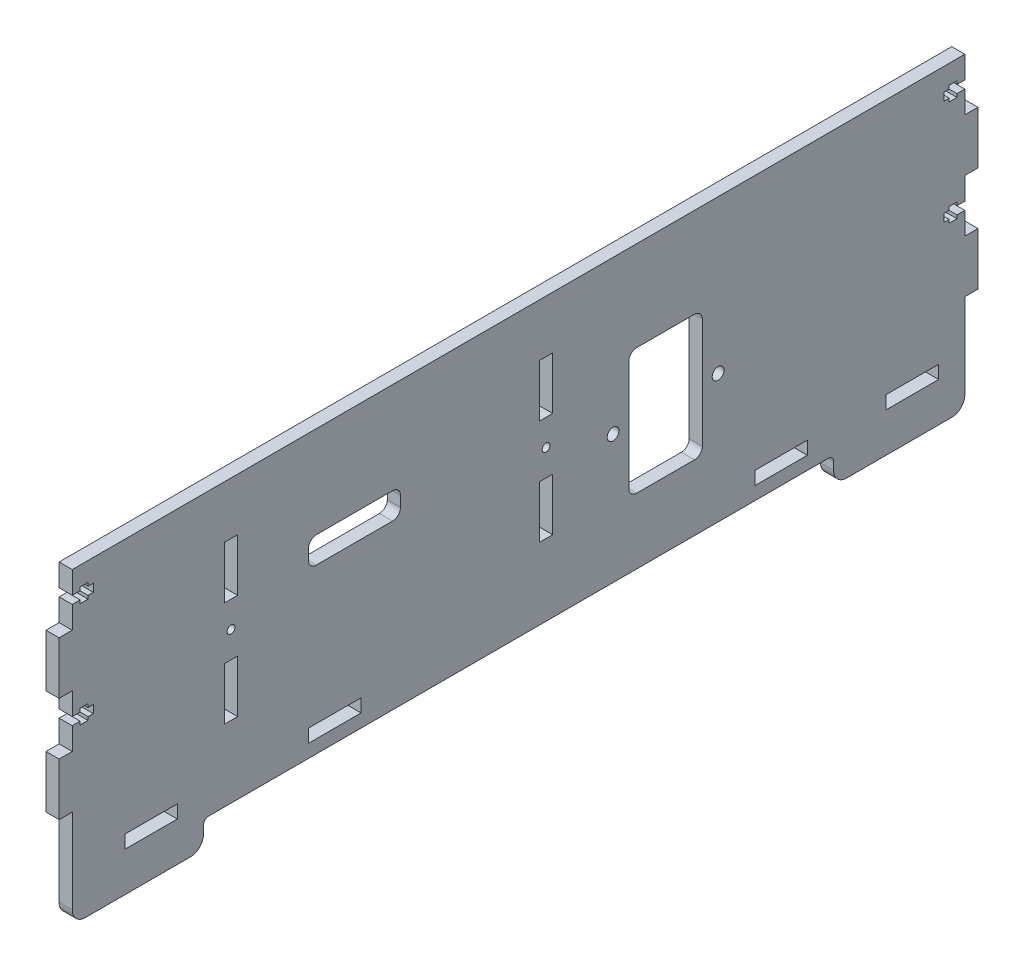
SolidWorks part; units mm, degrees
ref_plane "前视基准面" through (0, 0, 0) normal (0, 0, 1) x (1, 0, 0)
ref_plane "上视基准面" through (0, 0, 0) normal (0, 1, 0) x (1, 0, 0)
ref_plane "右视基准面" through (0, 0, 0) normal (1, 0, 0) x (0, 0, -1)
sketch "草图1" plane through (0, 0, 0) normal (1, 0, 0) x (0, 0, -1)
  line L0 (-168.5364, -19.7169) -> (-168.5364, -16.7169)
  line L1 (-218.5364, 92.5831) -> (121.4636, 92.5831)
  line L2 (-218.5364, 92.5831) -> (-218.5364, 84.0831)
  line L3 (-213.5364, -24.7169) -> (-173.5364, -24.7169)
  line L4 (121.4636, 92.5831) -> (121.4636, 84.0831)
  line L5 (-166.5364, -14.7169) -> (69.4636, -14.7169)
  line L6 (71.4636, -16.7169) -> (71.4636, -19.7169)
  line L7 (-223.5364, 100.1453) -> (-223.5364, -39.7846) construction
  line L8 (126.4636, -37.6236) -> (126.4636, 107.7498) construction
  line L9 (-218.5364, 52.5831) -> (-218.5364, 44.0831)
  line L10 (-223.5364, 72.5831) -> (-218.5364, 72.5831)
  line L11 (-223.5364, 72.5831) -> (-223.5364, 52.5831)
  line L12 (-223.5364, 52.5831) -> (-218.5364, 52.5831)
  line L13 (-218.5364, 12.5831) -> (-218.5364, -19.7169)
  line L14 (-223.5364, 32.5831) -> (-218.5364, 32.5831)
  line L15 (-223.5364, 32.5831) -> (-223.5364, 12.5831)
  line L16 (-223.5364, 12.5831) -> (-218.5364, 12.5831)
  line L17 (121.4636, 52.5831) -> (121.4636, 44.0831)
  line L18 (121.4636, 72.5831) -> (126.4636, 72.5831)
  line L19 (121.4636, 12.5831) -> (121.4636, -19.7169)
  line L20 (121.4636, 52.5831) -> (126.4636, 52.5831)
  line L21 (126.4636, 72.5831) -> (126.4636, 52.5831)
  line L22 (121.4636, 32.5831) -> (126.4636, 32.5831)
  line L23 (76.4636, -24.7169) -> (116.4636, -24.7169)
  line L24 (121.4636, 12.5831) -> (126.4636, 12.5831)
  line L25 (126.4636, 32.5831) -> (126.4636, 12.5831)
  line L26 (-160.5364, 123.2204) -> (-160.5364, -78.9999) construction
  line L27 (-35.5364, 116.7463) -> (-35.5364, -51.5802) construction
  line L28 (-198.5364, 109.7944) -> (-198.5364, -59.217) construction
  line L29 (-35.5364, 72.5831) -> (-40.5364, 72.5831)
  line L30 (-35.5364, 72.5831) -> (-35.5364, 52.5831)
  line L31 (-35.5364, 52.5831) -> (-40.5364, 52.5831)
  line L32 (-40.5364, 72.5831) -> (-40.5364, 52.5831)
  line L33 (-35.5364, 32.5831) -> (-40.5364, 32.5831)
  line L34 (-35.5364, 32.5831) -> (-35.5364, 12.5831)
  line L35 (-35.5364, 12.5831) -> (-40.5364, 12.5831)
  line L36 (-40.5364, 32.5831) -> (-40.5364, 12.5831)
  line L37 (-160.5364, 72.5831) -> (-155.5364, 72.5831)
  line L38 (-160.5364, 72.5831) -> (-160.5364, 52.5831)
  line L39 (-160.5364, 52.5831) -> (-155.5364, 52.5831)
  line L40 (-155.5364, 72.5831) -> (-155.5364, 52.5831)
  line L41 (-160.5364, 32.5831) -> (-155.5364, 32.5831)
  line L42 (-160.5364, 32.5831) -> (-160.5364, 12.5831)
  line L43 (-160.5364, 12.5831) -> (-155.5364, 12.5831)
  line L44 (-155.5364, 32.5831) -> (-155.5364, 12.5831)
  line L45 (-108.5364, 109.7944) -> (-108.5364, -59.217) construction
  line L46 (-108.5364, -9.7169) -> (162.8646, -9.7169) construction
  line L47 (-108.5364, -4.7169) -> (-128.5364, -4.7169)
  line L48 (-108.5364, -4.7169) -> (-108.5364, -9.7169)
  line L49 (-108.5364, -9.7169) -> (-128.5364, -9.7169)
  line L50 (-128.5364, -4.7169) -> (-128.5364, -9.7169)
  line L51 (-178.5364, -4.7169) -> (-198.5364, -4.7169)
  line L52 (-178.5364, -4.7169) -> (-178.5364, -9.7169)
  line L53 (-178.5364, -9.7169) -> (-198.5364, -9.7169)
  line L54 (-198.5364, -4.7169) -> (-198.5364, -9.7169)
  line L55 (121.4636, 84.0831) -> (118.4636, 84.0831)
  line L56 (111.4636, -9.7169) -> (91.4636, -9.7169)
  line L57 (111.4636, -9.7169) -> (111.4636, -4.7169)
  line L58 (111.4636, -4.7169) -> (91.4636, -4.7169)
  line L59 (91.4636, -9.7169) -> (91.4636, -4.7169)
  line L60 (61.4636, -9.7169) -> (41.4636, -9.7169)
  line L61 (61.4636, -9.7169) -> (61.4636, -4.7169)
  line L62 (61.4636, -4.7169) -> (41.4636, -4.7169)
  line L63 (41.4636, -9.7169) -> (41.4636, -4.7169)
  line L64 (18.4636, 58.2831) -> (-3.5364, 58.2831)
  line L65 (21.4636, 55.2831) -> (21.4636, 13.2831)
  line L66 (18.4636, 10.2831) -> (-3.5364, 10.2831)
  line L67 (-6.5364, 55.2831) -> (-6.5364, 13.2831)
  line L68 (-125.5364, 57.5831) -> (-96.5364, 57.5831)
  line L69 (-128.5364, 54.5831) -> (-128.5364, 50.5831)
  line L70 (-125.5364, 47.5831) -> (-96.5364, 47.5831)
  line L71 (-93.5364, 54.5831) -> (-93.5364, 50.5831)
  line L72 (118.4636, 84.0831) -> (118.4636, 85.3331)
  line L73 (118.4636, 85.3331) -> (115.4636, 85.3331)
  line L74 (115.4636, 85.3331) -> (115.4636, 84.0831)
  line L75 (115.4636, 84.0831) -> (113.4636, 84.0831)
  line L76 (113.4636, 84.0831) -> (113.4636, 81.0831)
  line L77 (113.4636, 81.0831) -> (115.4636, 81.0831)
  line L78 (115.4636, 81.0831) -> (115.4636, 79.8331)
  line L79 (115.4636, 79.8331) -> (118.4636, 79.8331)
  line L80 (118.4636, 79.8331) -> (118.4636, 81.0831)
  line L81 (118.4636, 81.0831) -> (121.4636, 81.0831)
  line L82 (121.4636, 81.0831) -> (121.4636, 72.5831)
  line L83 (121.4636, 44.0831) -> (118.4636, 44.0831)
  line L84 (118.4636, 44.0831) -> (118.4636, 45.3331)
  line L85 (118.4636, 45.3331) -> (115.4636, 45.3331)
  line L86 (115.4636, 45.3331) -> (115.4636, 44.0831)
  line L87 (115.4636, 44.0831) -> (113.4636, 44.0831)
  line L88 (113.4636, 44.0831) -> (113.4636, 41.0831)
  line L89 (113.4636, 41.0831) -> (115.4636, 41.0831)
  line L90 (115.4636, 41.0831) -> (115.4636, 39.8331)
  line L91 (115.4636, 39.8331) -> (118.4636, 39.8331)
  line L92 (118.4636, 39.8331) -> (118.4636, 41.0831)
  line L93 (118.4636, 41.0831) -> (121.4636, 41.0831)
  line L94 (121.4636, 41.0831) -> (121.4636, 32.5831)
  line L95 (-218.5364, 84.0831) -> (-215.5364, 84.0831)
  line L96 (-215.5364, 84.0831) -> (-215.5364, 85.3331)
  line L97 (-215.5364, 85.3331) -> (-212.5364, 85.3331)
  line L98 (-212.5364, 85.3331) -> (-212.5364, 84.0831)
  line L99 (-212.5364, 84.0831) -> (-210.5364, 84.0831)
  line L100 (-210.5364, 84.0831) -> (-210.5364, 81.0831)
  line L101 (-210.5364, 81.0831) -> (-212.5364, 81.0831)
  line L102 (-212.5364, 81.0831) -> (-212.5364, 79.8331)
  line L103 (-212.5364, 79.8331) -> (-215.5364, 79.8331)
  line L104 (-215.5364, 79.8331) -> (-215.5364, 81.0831)
  line L105 (-215.5364, 81.0831) -> (-218.5364, 81.0831)
  line L106 (-218.5364, 81.0831) -> (-218.5364, 72.5831)
  line L107 (-218.5364, 44.0831) -> (-215.5364, 44.0831)
  line L108 (-215.5364, 44.0831) -> (-215.5364, 45.3331)
  line L109 (-215.5364, 45.3331) -> (-212.5364, 45.3331)
  line L110 (-212.5364, 45.3331) -> (-212.5364, 44.0831)
  line L111 (-212.5364, 44.0831) -> (-210.5364, 44.0831)
  line L112 (-210.5364, 44.0831) -> (-210.5364, 41.0831)
  line L113 (-210.5364, 41.0831) -> (-212.5364, 41.0831)
  line L114 (-212.5364, 41.0831) -> (-212.5364, 39.8331)
  line L115 (-212.5364, 39.8331) -> (-215.5364, 39.8331)
  line L116 (-215.5364, 39.8331) -> (-215.5364, 41.0831)
  line L117 (-215.5364, 41.0831) -> (-218.5364, 41.0831)
  line L118 (-218.5364, 41.0831) -> (-218.5364, 32.5831)
  arc A0 (116.4636, -24.7169) -> (121.4636, -19.7169) centre (116.4636, -19.7169) ccw
  arc A1 (71.4636, -19.7169) -> (76.4636, -24.7169) centre (76.4636, -19.7169) ccw
  arc A2 (-168.5364, -19.7169) -> (-173.5364, -24.7169) centre (-173.5364, -19.7169) cw
  arc A3 (-218.5364, -19.7169) -> (-213.5364, -24.7169) centre (-213.5364, -19.7169) ccw
  arc A4 (69.4636, -14.7169) -> (71.4636, -16.7169) centre (69.4636, -16.7169) cw
  arc A5 (-168.5364, -16.7169) -> (-166.5364, -14.7169) centre (-166.5364, -16.7169) cw
  arc A6 (18.4636, 58.2831) -> (21.4636, 55.2831) centre (18.4636, 55.2831) cw
  arc A7 (-3.5364, 58.2831) -> (-6.5364, 55.2831) centre (-3.5364, 55.2831) ccw
  arc A8 (-3.5364, 10.2831) -> (-6.5364, 13.2831) centre (-3.5364, 13.2831) cw
  arc A9 (21.4636, 13.2831) -> (18.4636, 10.2831) centre (18.4636, 13.2831) cw
  circle A10 centre (27.4636, 34.2831) radius 2.25
  circle A11 centre (-12.5364, 34.2831) radius 2.25
  arc A12 (-125.5364, 57.5831) -> (-128.5364, 54.5831) centre (-125.5364, 54.5831) ccw
  arc A13 (-128.5364, 50.5831) -> (-125.5364, 47.5831) centre (-125.5364, 50.5831) ccw
  arc A14 (-96.5364, 47.5831) -> (-93.5364, 50.5831) centre (-96.5364, 50.5831) ccw
  arc A15 (-96.5364, 57.5831) -> (-93.5364, 54.5831) centre (-96.5364, 54.5831) cw
  circle A16 centre (-38.0364, 42.5831) radius 1.5
  circle A17 centre (-158.0364, 42.5831) radius 1.5
  point P60 (-38.0364, 32.5831)
  point P73 (-108.5364, -7.2169)
  point P89 (21.4636, 58.2831)
  point P92 (-6.5364, 58.2831)
  point P97 (21.4636, 10.2831)
  point P126 (119.9636, 81.0831)
  point P151 (-217.0364, 81.0831)
  dimension "D14" = 5
  dimension "D15" = 2
  dimension "D46" = 40
  dimension "D45" = 3
  dimension "D49" = 3
  dimension "D70" = 2.5
  dimension "D1" = 5
  dimension "D2" = 5
  dimension "D3" = 20
  dimension "D4" = 20
  dimension "D5" = 20
  dimension "D6" = 20
  dimension "D7" = 20
  dimension "D8" = 20
  dimension "D9" = 20
  dimension "D10" = 20
  dimension "D11" = 50
  dimension "D12" = 50
  dimension "D13" = 10
  dimension "D16" = 58
  dimension "D17" = 125
  dimension "D18" = 5
  dimension "D19" = 5
  dimension "D20" = 5
  dimension "D21" = 5
  dimension "D22" = 20
  dimension "D23" = 20
  dimension "D24" = 20
  dimension "D25" = 20
  dimension "D26" = 20
  dimension "D27" = 20
  dimension "D28" = 20
  dimension "D29" = 20
  dimension "D30" = 20
  dimension "D31" = 90
  dimension "D32" = 20
  dimension "D33" = 20
  dimension "D34" = 5
  dimension "D35" = 5
  dimension "D36" = 0
  dimension "D37" = 0
  dimension "D38" = 5
  dimension "D39" = 5
  dimension "D40" = 10
  dimension "D41" = 28
  dimension "D42" = 48
  dimension "D43" = 25
  dimension "D44" = 100
  dimension "D47" = 6
  dimension "D48" = 24
  dimension "D50" = 35
  dimension "D51" = 3
  dimension "D52" = 3
  dimension "D53" = 5.5
  dimension "D54" = 8.5
  dimension "D55" = 1.25
  dimension "D56" = 1.25
  dimension "D57" = 8.5
  dimension "D58" = 5.5
  dimension "D59" = 3
  dimension "D60" = 3
  dimension "D61" = 3
  dimension "D62" = 1.25
  dimension "D63" = 1.25
  dimension "D64" = 3
  dimension "D65" = 3
  dimension "D66" = 5.5
  dimension "D67" = 1.25
  dimension "D68" = 1.25
  dimension "D69" = 8.5
  dimension "D71" = 2.5
  dimension "D72" = 10
  dimension "D73" = 10
extrude "凸台-拉伸1" add sketch "草图1" along normal blind 5
